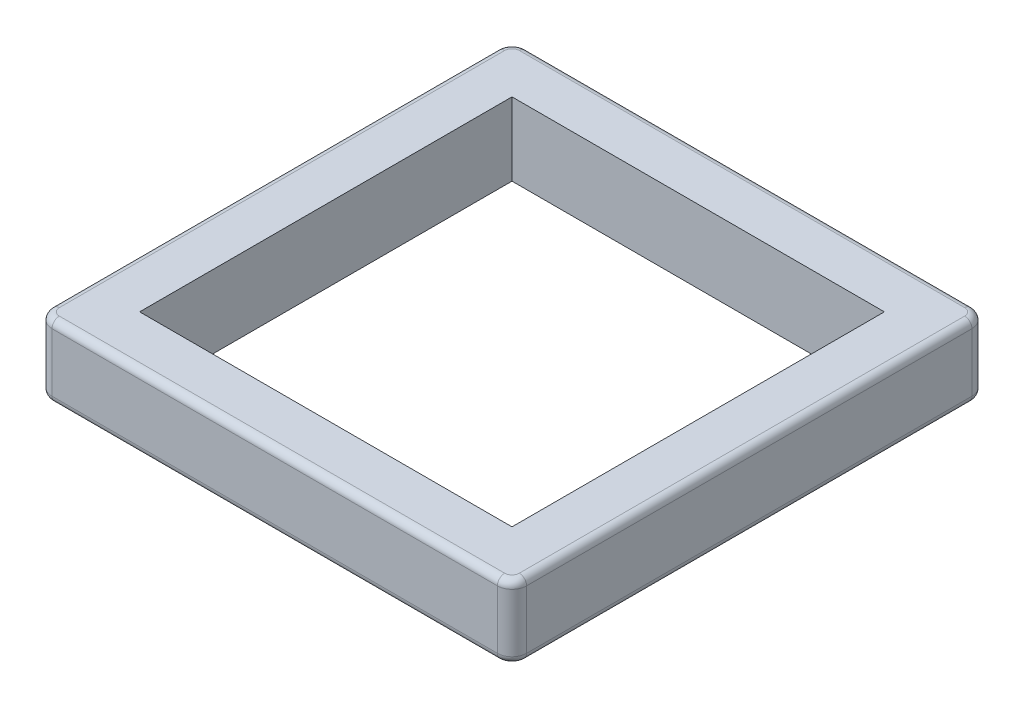
SolidWorks part; units mm, degrees
ref_plane "Front Plane" through (0, 0, 0) normal (0, 0, 1) x (1, 0, 0)
ref_plane "Top Plane" through (0, 0, 0) normal (0, 1, 0) x (1, 0, 0)
ref_plane "Right Plane" through (0, 0, 0) normal (1, 0, 0) x (0, 0, -1)
sketch "Sketch1" plane through (0, 0, 0) normal (0, 1, 0) x (1, 0, 0)
  line L1 (-323.85, -323.85) -> (323.85, -323.85)
  line L2 (-323.85, -323.85) -> (-323.85, 323.85)
  line L3 (-323.85, 323.85) -> (323.85, 323.85)
  line L4 (323.85, -323.85) -> (323.85, 323.85)
  line L5 (-323.85, -323.85) -> (323.85, 323.85) construction
  line L6 (-323.85, 323.85) -> (323.85, -323.85) construction
  line L7 (-412.75, -412.75) -> (412.75, -412.75)
  line L8 (-412.75, -412.75) -> (-412.75, 412.75)
  line L9 (-412.75, 412.75) -> (412.75, 412.75)
  line L10 (412.75, -412.75) -> (412.75, 412.75)
  line L11 (-412.75, -412.75) -> (412.75, 412.75) construction
  line L12 (-412.75, 412.75) -> (412.75, -412.75) construction
  point P0 (0, 0)
  point P6 (0, 0)
  dimension "D1" = 647.7
  dimension "D2" = 647.7
  dimension "D3" = 88.9
  dimension "D4" = 88.9
extrude "Boss-Extrude1" add sketch "Sketch1" along normal blind 127
fillet "Fillet1" radius 25.4 4 edges at (-412.75, 63.5, -412.75) (-412.75, 63.5, 412.75) (412.75, 63.5, -412.75) (412.75, 63.5, 412.75)
fillet "Fillet2" radius 12.7 16 edges at (405.3105, 0, -405.3105) (412.75, 0, 0) (405.3105, 0, 405.3105) (0, 0, 412.75) (-405.3105, 0, 405.3105) (-412.75, 0, 0) (-405.3105, 0, -405.3105) (405.3105, 127, -405.3105) (412.75, 127, 0) (405.3105, 127, 405.3105) (0, 127, 412.75) (-405.3105, 127, 405.3105) (-412.75, 127, 0) (-405.3105, 127, -405.3105) (0, 0, -412.75) (0, 127, -412.75)
sketch "Sketch2" plane through (-412.75, 0, 0) normal (-1, 0, 0) x (0, 0, 1)
  text T0 "3792" font "Paladins Straight" height 76.2
extrude "Cut-Extrude1" cut sketch "Sketch2" against normal blind 5.08
